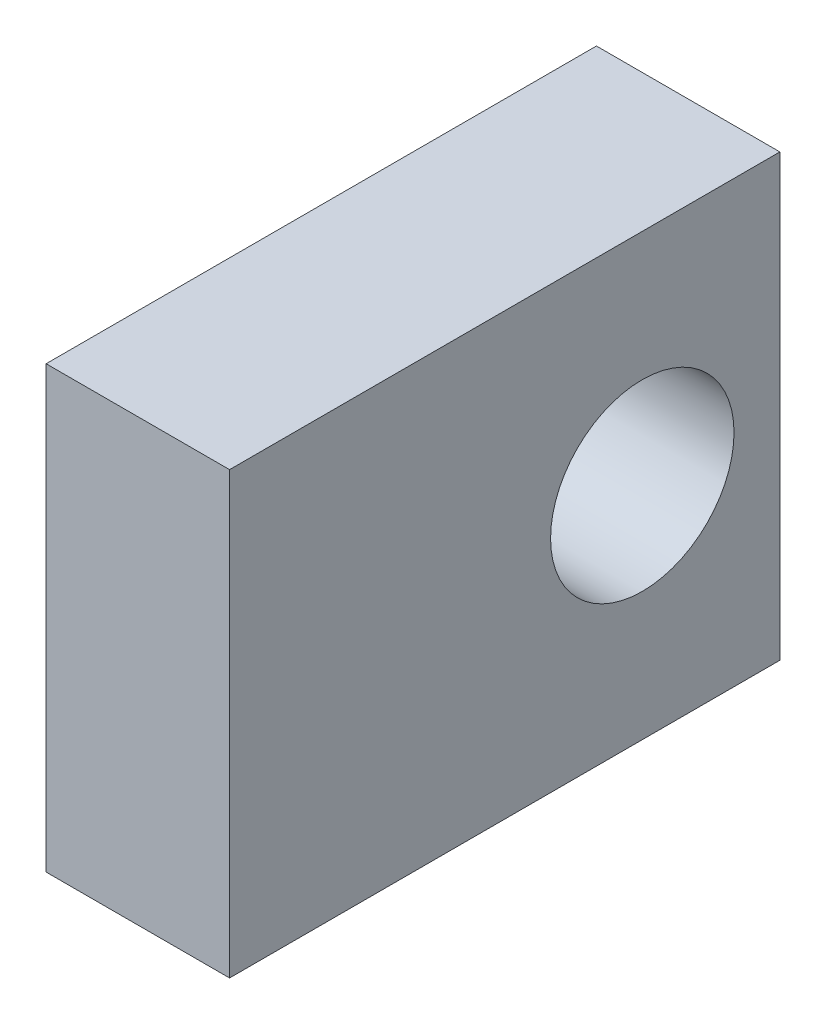
SolidWorks part; units mm, degrees
material "AISI 1020"
ref_plane "Front Plane" through (0, 0, 0) normal (0, 0, 1) x (1, 0, 0)
ref_plane "Top Plane" through (0, 0, 0) normal (0, 1, 0) x (1, 0, 0)
ref_plane "Right Plane" through (0, 0, 0) normal (1, 0, 0) x (0, 0, -1)
sketch "Sketch1" plane through (0, 0, 0) normal (1, 0, 0) x (0, 0, -1)
  line L1 (-19.05, -15.24) -> (19.05, -15.24)
  line L2 (-19.05, -15.24) -> (-19.05, 15.24)
  line L3 (-19.05, 15.24) -> (19.05, 15.24)
  line L4 (19.05, -15.24) -> (19.05, 15.24)
  line L5 (-19.05, -15.24) -> (19.05, 15.24) construction
  line L6 (-19.05, 15.24) -> (19.05, -15.24) construction
  circle A0 centre (9.525, 0) radius 6.35
  point P0 (0, 0)
  dimension "D3" = 12.7
  dimension "D4" = 9.525
  dimension "D1" = 38.1
  dimension "D2" = 30.48
extrude "Boss-Extrude1" add sketch "Sketch1" along normal blind 12.7
